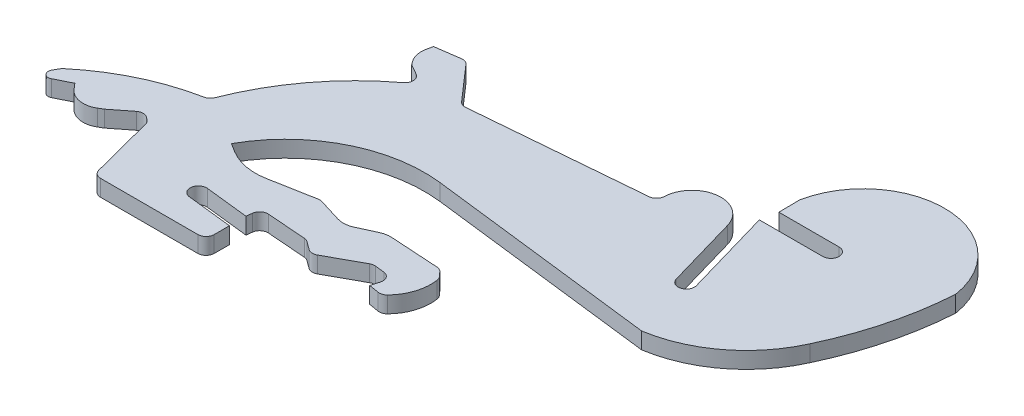
SolidWorks part; units mm, degrees
ref_plane "Front Plane" through (0, 0, 0) normal (0, 0, 1) x (1, 0, 0)
ref_plane "Top Plane" through (0, 0, 0) normal (0, 1, 0) x (1, 0, 0)
ref_plane "Right Plane" through (0, 0, 0) normal (1, 0, 0) x (0, 0, -1)
sketch "Sketch2" plane through (0, 0, 0) normal (0, 1, 0) x (1, 0, 0)
  line L28 (-42.5, 9.8153) -> (-40.2, 13.8486)
  line L29 (-36.6807, 12.7037) -> (-42.5, 9.8153)
  line L30 (-33.582, 9.1153) -> (-36.6807, 12.7037)
  line L31 (-29.8788, 11.3129) -> (-33.582, 9.1153)
  line L32 (4.26, 16.67) -> (10.265, 14.8219)
  line L33 (0, 0) -> (-20.44, 0)
  line L34 (22.2697, 7.6463) -> (24.8125, 7.2216)
  line L35 (23.2053, 10.8574) -> (22.2697, 7.6463)
  line L36 (19.2552, 11.2976) -> (23.2053, 10.8574)
  line L37 (11.8276, 7.2216) -> (19.2552, 11.2976)
  line L38 (9.25, 9.1) -> (11.8276, 7.2216)
  line L39 (0, 7.2986) -> (0.2788, 9.8)
  line L40 (-7.9231, 8.1815) -> (0, 7.2986)
  line L41 (0, 4.28) -> (-8.2554, 5.2)
  line L42 (0, 0) -> (0, 4.28)
  line L43 (-7.9231, 14.42) -> (4.26, 16.67)
  line L44 (-12.82, 17.46) -> (-7.9231, 14.42)
  line L45 (0.2788, 9.8) -> (9.25, 9.1)
  line L46 (10.265, 14.8219) -> (15.6812, 17.3217)
  line L47 (15.6812, 17.3217) -> (26.1051, 16.67)
  line L48 (26.1051, 16.67) -> (27.5, 15.12)
  line L49 (-20.44, 0) -> (-23.89, 13.229)
  line L50 (-23.89, 13.229) -> (-25.72, 14.58)
  line L51 (-25.72, 14.58) -> (-29.8788, 11.3129)
  line L52 (-4.89, 44.16) -> (-8.851, 46.4354)
  line L53 (-8.851, 46.4354) -> (-10.31, 48.4337)
  line L54 (-10.31, 48.4337) -> (-9.7196, 51.2866)
  line L55 (-9.7196, 51.2866) -> (-4.45, 52.03)
  line L56 (-4.45, 52.03) -> (2.1, 44.53)
  line L57 (2.1, 44.53) -> (35.22, 47.35)
  line L58 (12.44, 30.35) -> (54.32, 25.29)
  line L60 (48.0716, 56.63) -> (48.0108, 60.48)
  line L61 (52.1624, 37.4514) -> (49.2985, 47.38)
  line L62 (45.4508, 49.8957) -> (49.2717, 36.6497)
  line L63 (47.4956, 53.63) -> (49.2985, 47.38)
  line L64 (59.0716, 53.63) -> (47.4956, 53.63)
  line L65 (48.0716, 56.63) -> (59.0716, 56.63)
  arc A13 (-40.2, 13.8486) -> (-21.88, 22.46) centre (-15.2463, -15.4452) cw
  arc A14 (-21.88, 22.46) -> (-4.89, 44.16) centre (20.3443, 6.9017) cw
  arc A15 (24.8125, 7.2216) -> (27.5, 15.12) centre (19.6156, 13.3963) ccw
  arc A16 (-8.2554, 5.2) -> (-7.9231, 8.1815) centre (-8.0892, 6.6908) cw
  arc A17 (35.22, 47.35) -> (45.4508, 49.8957) centre (40.3825, 48.4337) cw
  arc A18 (49.2717, 36.6497) -> (52.1624, 37.4514) centre (50.7129, 37.0655) ccw
  arc A19 (59.0716, 56.63) -> (59.0716, 53.63) centre (59.0716, 55.13) cw
  arc A20 (48.0108, 60.48) -> (77.21, 59.8) centre (62.5507, 57.5772) cw
  arc A21 (77.21, 59.8) -> (71.72, 38.62) centre (18.8379, 63.6289) cw
  arc A22 (71.72, 38.62) -> (54.32, 25.29) centre (50.6354, 48.1209) cw
  arc A23 (12.44, 30.35) -> (-12.82, 17.46) centre (9.3925, 5.1266) ccw
  point P0 (77.21, 59.8)
  point P3 (51.1138, 35.62)
  point P4 (0, 0)
  point P5 (71.72, 38.62)
  point P6 (54.32, 25.29)
  point P8 (-4.89, 44.16)
  point P14 (12.44, 30.35)
  point P20 (35.22, 47.35)
  point P35 (0, 0)
  point P38 (57.5716, 55.13)
  point P41 (0, 0)
  point P50 (0, 0)
  point P51 (71.72, 38.62)
  point P52 (0, 0)
  point P53 (62.8959, 72.4)
  point P54 (0, 0)
  point P55 (0, 0)
  point P56 (0, 0)
  point P57 (0, 0)
  point P60 (-9.0194, 46.5093)
  point P64 (-7.9231, 43.5262)
  point P66 (-9.0118, 49.5016)
  point P68 (-3.8674, 52.03)
  point P70 (-9.5158, 50.7404)
  point P72 (-6.7218, 46.2968)
  point P73 (0.2788, 44.16)
  point P75 (0, 0)
  point P77 (4.26, 44.16)
  point P79 (-10.31, 48.4337)
  point P81 (-9.7196, 51.2866)
  point P83 (-8.851, 46.4354)
  point P85 (50.7231, 37.5023)
  point P87 (52.1624, 37.0655)
  point P102 (27.5, 15.12)
  dimension "D6" = 53.63
  dimension "D11" = 9.8
  dimension "D32" = 17.46
  dimension "D33" = 12.82
  dimension "D34" = 4.26
  dimension "D35" = 21.88
  dimension "D36" = 22.46
  dimension "D37" = 25.72
  dimension "D38" = 67.7
  dimension "D39" = 4.89
  dimension "D40" = 44.16
  dimension "D75" = 14.8219
  dimension "D2" = 38.4812
  dimension "D4" = 20.44
  dimension "D5" = 8.0706
  dimension "D10" = 16.67
  dimension "D45" = 5.275
  dimension "D47" = 1.5
  dimension "D61" = 44.9994
  dimension "D62" = 14.8268
  dimension "D63" = 58.4976
  dimension "D64" = 23.1263
  dimension "D7" = 77.21
  dimension "D8" = 59.8
  dimension "D9" = 35.62
  dimension "D12" = 14.42
  dimension "D13" = 9.1
  dimension "D14" = 11.8276
  dimension "D15" = 14.58
  dimension "D16" = 19.2552
  dimension "D17" = 19.6156
  dimension "D18" = 73.91
  dimension "D19" = 22.2697
  dimension "D20" = 23.89
  dimension "D21" = 23.2053
  dimension "D22" = 24.8125
  dimension "D23" = 27.5
  dimension "D24" = 7.9231
  dimension "D25" = 8.0892
  dimension "D26" = 9.25
  dimension "D27" = 4.28
  dimension "D28" = 7.2216
  dimension "D29" = 7.6463
  dimension "D30" = 25.29
  dimension "D31" = 11.2976
  dimension "D41" = 44.53
  dimension "D42" = 47.35
  dimension "D43" = 52.03
  dimension "D44" = 35.22
  dimension "D46" = 6.25
  dimension "D48" = 10.076
  dimension "D49" = 54.32
  dimension "D50" = 38.62
  dimension "D51" = 3.85
  dimension "D52" = 71.72
  dimension "D53" = 30.35
  dimension "D54" = 12.44
  dimension "D55" = 72.4
  dimension "D56" = 11
  dimension "D57" = 10.31
  dimension "D58" = 2.1
  dimension "D59" = 4.45
  dimension "D60" = 70
  dimension "D65" = 10.265
  dimension "D66" = 15.6812
  dimension "D67" = 26.1051
  dimension "D68" = 40.3825
  dimension "D69" = 47.4956
  dimension "D70" = 9.1153
  dimension "D71" = 9.8153
  dimension "D72" = 11.3129
  dimension "D73" = 12.7037
  dimension "D74" = 13.229
  dimension "D76" = 17.3217
  dimension "D77" = 8.851
  dimension "D78" = 9.7196
  dimension "D79" = 15.2463
  dimension "D80" = 29.8788
  dimension "D81" = 33.582
  dimension "D82" = 36.6807
  dimension "D86" = 46.4354
  dimension "D87" = 51.2866
extrude "Boss-Extrude1" add sketch "Sketch2" along normal blind 3
fillet "Fillet1" radius 10 1 edges at (-7.9231, 1.5, -14.42)
fillet "Fillet2" radius 1 1 edges at (-42.5, 1.5, -9.8153)
fillet "Fillet3" radius 1.5 18 edges at (35.22, 1.5, -47.35) (-20.44, 1.5, 0) (0, 1.5, 0) (0.2788, 1.5, -9.8) (9.25, 1.5, -9.1) (19.2552, 1.5, -11.2976) (11.8276, 1.5, -7.2216) (26.1051, 1.5, -16.67) (27.5, 1.5, -15.12) (24.8125, 1.5, -7.2216) (23.2053, 1.5, -10.8574) (4.26, 1.5, -16.67) (-21.88, 1.5, -22.46) (-25.72, 1.5, -14.58) (-23.89, 1.5, -13.229) (-4.89, 1.5, -44.16) (-4.45, 1.5, -52.03) (2.1, 1.5, -44.53)
fillet "Fillet4" radius 4 2 edges at (-10.31, 1.5, -48.4337) (-33.582, 1.5, -9.1153)
fillet "Fillet5" radius 4 2 edges at (10.265, 1.5, -14.8219) (15.6812, 1.5, -17.3217)
